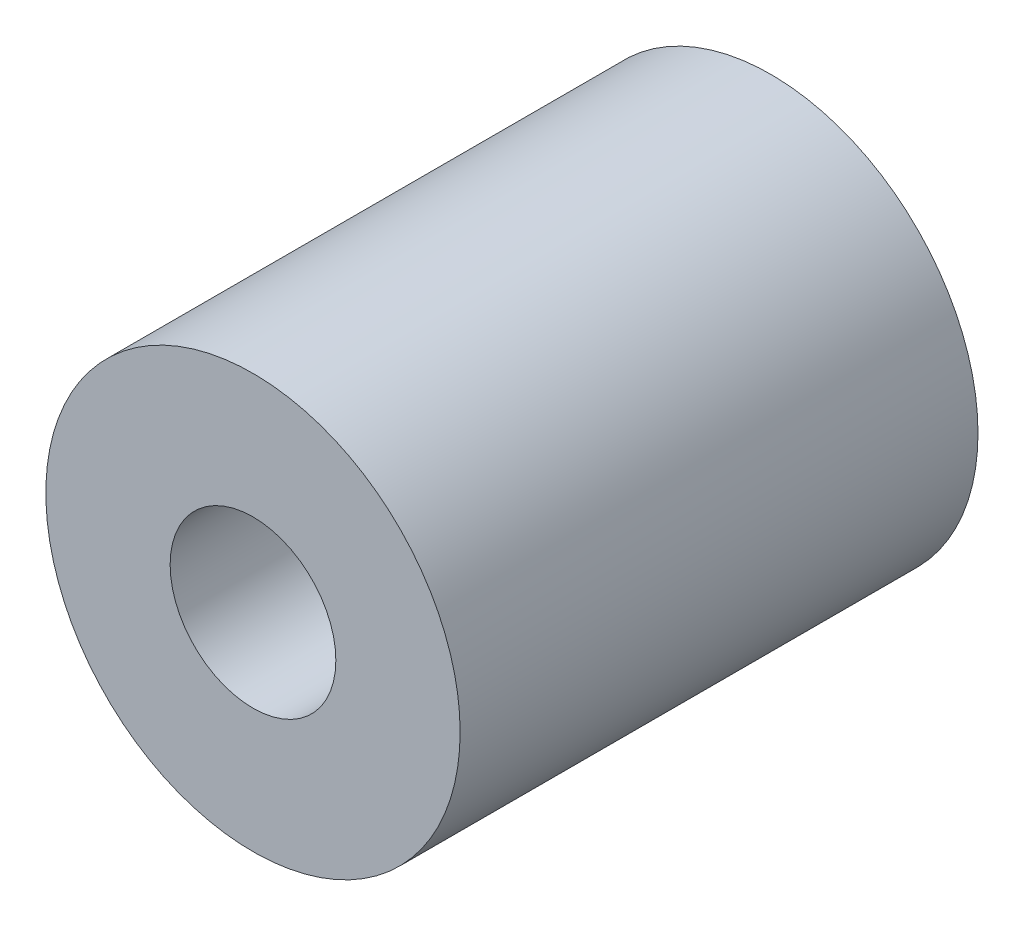
SolidWorks part; units mm, degrees
ref_plane "前视基准面" through (0, 0, 0) normal (0, 0, 1) x (1, 0, 0)
ref_plane "上视基准面" through (0, 0, 0) normal (0, 1, 0) x (1, 0, 0)
ref_plane "右视基准面" through (0, 0, 0) normal (1, 0, 0) x (0, 0, -1)
sketch "草图1" plane through (0, 0, 0) normal (0, 0, 1) x (1, 0, 0)
  circle A0 centre (0, 0) radius 10
  dimension "D1" = 20
extrude "凸台-拉伸1" add sketch "草图1" along normal blind 25
sketch "草图3" plane through (0, 0, 25) normal (0, 0, 1) x (1, 0, 0)
  circle A0 centre (0, 0) radius 4
  dimension "D1" = 8
extrude "切除-拉伸1" cut sketch "草图3" against normal blind 7.5
sketch "草图4" plane through (0, 0, 0) normal (0, 0, -1) x (-1, 0, 0)
  circle A0 centre (0, 0) radius 5
  dimension "D1" = 10
extrude "切除-拉伸2" cut sketch "草图4" against normal blind 12.5
sketch "草图5" plane through (0, 0, 17.5) normal (0, 0, 1) x (1, 0, 0)
  circle A1 centre (0, 0) radius 4
  circle A2 centre (0, 0) radius 4
  dimension "D1" = 0
extrude "切除-拉伸3" cut sketch "草图5" against normal through all
